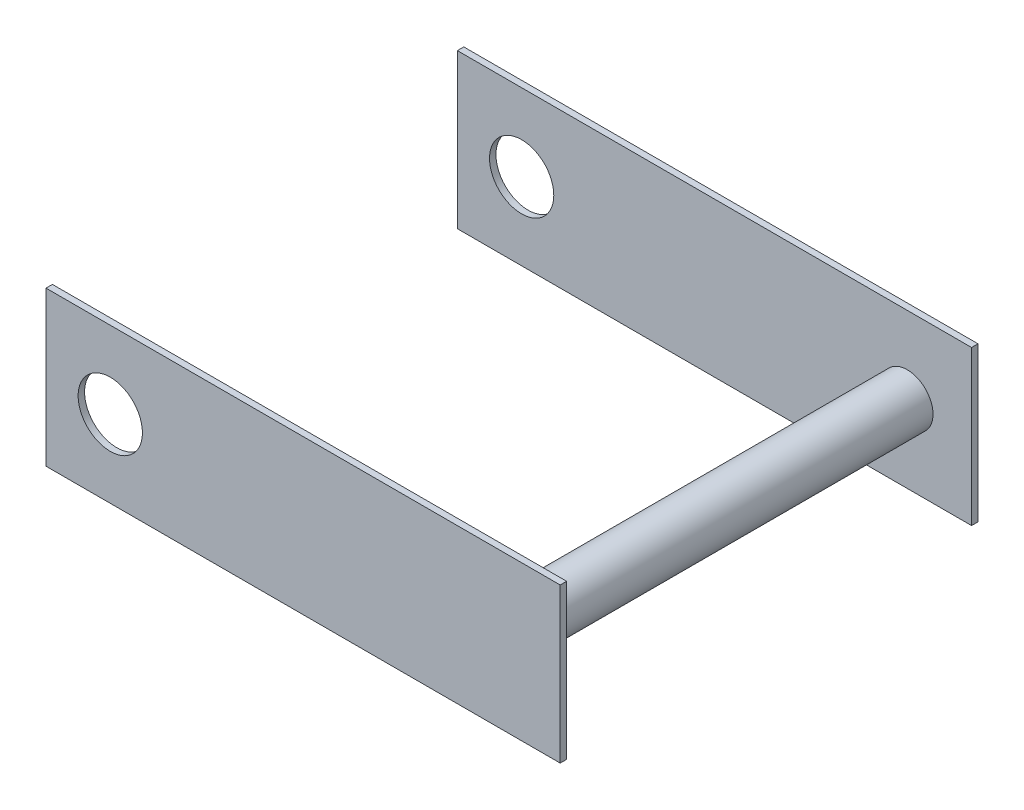
SolidWorks part; units mm, degrees
ref_plane "Front Plane" through (0, 0, 0) normal (0, 0, 1) x (1, 0, 0)
ref_plane "Top Plane" through (0, 0, 0) normal (0, 1, 0) x (1, 0, 0)
ref_plane "Right Plane" through (0, 0, 0) normal (1, 0, 0) x (0, 0, -1)
sketch "Sketch2" plane through (0, 0, 0) normal (0, 0, 1) x (1, 0, 0)
  line L4 (63.5, 38.1) -> (-63.5, 38.1)
  line L5 (63.5, -38.1) -> (63.5, 38.1)
  line L6 (-63.5, -38.1) -> (63.5, -38.1)
  line L7 (-63.5, 38.1) -> (-63.5, -38.1)
  line L8 (63.5, 38.1) -> (-63.5, 38.1)
  line L9 (63.5, -38.1) -> (63.5, 38.1)
  line L10 (-63.5, -38.1) -> (63.5, -38.1)
  line L11 (-63.5, 38.1) -> (-63.5, -38.1)
  circle A1 centre (25.4, 0) radius 12.7
  circle A2 centre (25.4, 0) radius 12.7
  dimension "D1" = 0
  dimension "D2" = 0
sketch "Sketch3" plane through (0, 0, 0) normal (0, 1, 0) x (1, 0, 0)
  line L4 (-63.5, 12.7) -> (-63.5, -25.4)
  line L5 (-63.5, -25.4) -> (63.5, -25.4)
  line L6 (63.5, -25.4) -> (63.5, 0)
  line L7 (-18.5941, 12.7) -> (-63.5, 12.7)
  line L8 (-63.5, 12.7) -> (-63.5, -25.4)
  line L9 (-63.5, -25.4) -> (63.5, -25.4)
  line L10 (63.5, -25.4) -> (63.5, 0)
  line L11 (-18.5941, 12.7) -> (-63.5, 12.7)
  arc A3 (63.5, 0) -> (25.4, 38.1) centre (25.4, 0) ccw
  arc A4 (25.4, 38.1) -> (-7.5956, 19.05) centre (25.4, 0) ccw
  arc A5 (-18.5941, 12.7) -> (-7.5956, 19.05) centre (-18.5941, 25.4) ccw
  arc A6 (63.5, 0) -> (25.4, 38.1) centre (25.4, 0) ccw
  arc A7 (25.4, 38.1) -> (-7.5956, 19.05) centre (25.4, 0) ccw
  arc A8 (-18.5941, 12.7) -> (-7.5956, 19.05) centre (-18.5941, 25.4) ccw
  dimension "D1" = 0
sketch "Sketch6" plane through (0, 0, 0) normal (0, 1, 0) x (1, 0, 0)
  line L0 (25.4, 88.9) -> (25.4, -76.2) construction
  line L1 (25.4, 88.9) -> (25.4, -76.2)
sketch "Sketch4" plane through (0, 0, 0) normal (0, 0, 1) x (1, 0, 0)
  circle A0 centre (25.4, 0) radius 12.7 construction
  circle A1 centre (25.4, 0) radius 12.7 construction
  circle A2 centre (25.4, 0) radius 10.16
  dimension "D1" = 2.54
extrude "Boss-Extrude1" add sketch "Sketch4" along normal up to vertex (76.2 mm away) and the other way up to vertex (88.9 mm away) up to point (25.4, 0, 76.2) other way up to point (25.4, 0, -88.9)
sketch "Sketch7" plane through (0, 0, -88.9) normal (0, 0, -1) x (-1, 0, 0)
  line L0 (152.4, 30.48) -> (152.4, -30.48) construction
  line L1 (-50.8, -30.48) -> (152.4, -30.48)
  line L2 (-50.8, -30.48) -> (-50.8, 30.48)
  line L3 (-50.8, 30.48) -> (152.4, 30.48)
  line L4 (152.4, -30.48) -> (152.4, 30.48)
  line L5 (152.4, -30.48) -> (63.5, -30.48) construction
  dimension "D1" = 25.4
extrude "Boss-Extrude2" add sketch "Sketch7" against normal blind 2.54
sketch "Sketch8" plane through (0, 0, 76.2) normal (0, 0, 1) x (1, 0, 0)
  line L4 (50.8, -30.48) -> (50.8, 30.48)
  line L5 (50.8, 30.48) -> (-152.4, 30.48)
  line L6 (-152.4, 30.48) -> (-152.4, -30.48)
  line L7 (-152.4, -30.48) -> (50.8, -30.48)
  line L8 (50.8, -30.48) -> (50.8, 30.48)
  line L9 (50.8, 30.48) -> (-152.4, 30.48)
  line L10 (-152.4, 30.48) -> (-152.4, -30.48)
  line L11 (-152.4, -30.48) -> (50.8, -30.48)
  dimension "D1" = 0
extrude "Boss-Extrude3" add sketch "Sketch8" against normal blind 2.54
sketch "Sketch9" plane through (0, 0, 76.2) normal (0, 0, 1) x (1, 0, 0)
  line L0 (-152.4, 0) -> (-127, 0) construction
  line L1 (-152.4, 30.48) -> (-152.4, -30.48) construction
  circle A0 centre (-127, 0) radius 12.7
  dimension "D1" = 25.4
  dimension "D2" = 25.4
extrude "Cut-Extrude1" cut sketch "Sketch9" against normal through all
